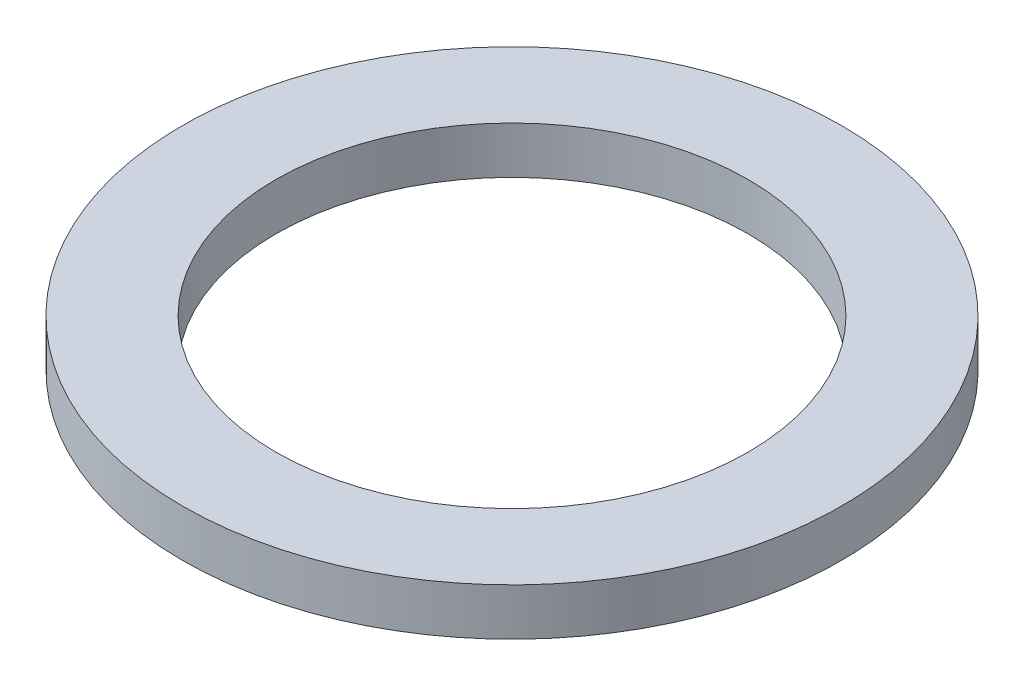
SolidWorks part; units mm, degrees
ref_plane "Front Plane" through (0, 0, 0) normal (0, 0, 1) x (1, 0, 0)
ref_plane "Top Plane" through (0, 0, 0) normal (0, 1, 0) x (1, 0, 0)
ref_plane "Right Plane" through (0, 0, 0) normal (1, 0, 0) x (0, 0, -1)
sketch "Sketch1" plane through (0, 0, 0) normal (0, 1, 0) x (1, 0, 0)
  circle A0 centre (0, 0) radius 7.9629
  circle A1 centre (0, 0) radius 11.1125
  dimension "D1" = 15.9258
  dimension "D2" = 22.225
extrude "Boss-Extrude1" add sketch "Sketch1" along normal blind 1.5875
